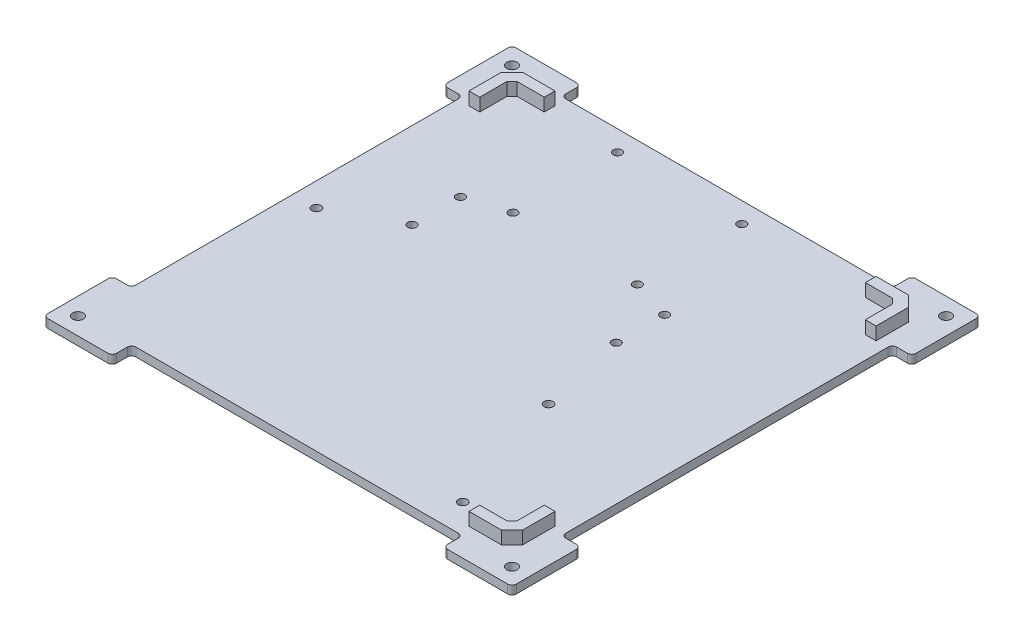
SolidWorks part; units mm, degrees
ref_plane "Plan de face" through (0, 0, 0) normal (0, 0, 1) x (1, 0, 0)
ref_plane "Plan de dessus" through (0, 0, 0) normal (0, 1, 0) x (1, 0, 0)
ref_plane "Plan de droite" through (0, 0, 0) normal (1, 0, 0) x (0, 0, -1)
sketch "Esquisse1" plane through (0, 0, 0) normal (0, 1, 0) x (1, 0, 0)
  line L20 (32, 234.4934) -> (32, -21.6261) construction
  line L21 (0, 0) -> (218, 0) construction
  line L22 (0, 0) -> (0, 218) construction
  line L23 (0, 218) -> (218, 218) construction
  line L24 (218, 0) -> (218, 218) construction
  line L25 (9, 209) -> (209, 209) construction
  line L26 (9, 209) -> (9, 9) construction
  line L27 (9, 9) -> (209, 9) construction
  line L28 (209, 209) -> (209, 9) construction
  line L29 (186, 234.4934) -> (186, -24.8818) construction
  line L30 (-33.4451, 186) -> (261.3817, 186) construction
  line L31 (-37.0626, 32) -> (249.4439, 32) construction
  line L32 (0, 218) -> (0, 186)
  line L33 (0, 186) -> (9, 186)
  line L35 (9, 32) -> (0, 32)
  line L36 (0, 32) -> (0, 0)
  line L37 (0, 0) -> (32, 0)
  line L38 (32, 0) -> (32, 9)
  line L39 (32, 9) -> (186, 9)
  line L40 (186, 9) -> (186, 0)
  line L41 (186, 0) -> (218, 0)
  line L42 (218, 0) -> (218, 32)
  line L43 (218, 32) -> (209, 32)
  line L44 (209, 32) -> (209, 186)
  line L45 (209, 186) -> (218, 186)
  line L46 (218, 186) -> (218, 218)
  line L47 (218, 218) -> (186, 218)
  line L48 (186, 218) -> (186, 209)
  line L50 (32, 209) -> (32, 218)
  line L51 (32, 218) -> (0, 218)
  line L60 (186, 209) -> (32, 209)
  line L61 (9, 186) -> (9, 32)
  circle A0 centre (8, 210) radius 2.5
  circle A1 centre (210, 210) radius 2.5
  circle A2 centre (210, 8) radius 2.5
  circle A3 centre (8, 8) radius 2.5
  point P35 (109, 109)
  point P45 (109, 109)
  point P54 (109, 109)
  dimension "D11" = 5
  dimension "D1" = 218
  dimension "D2" = 218
  dimension "D3" = 9
  dimension "D4" = 9
  dimension "D5" = 9
  dimension "D6" = 9
  dimension "D7" = 32
  dimension "D8" = 32
  dimension "D9" = 32
  dimension "D10" = 32
  dimension "D12" = 8
  dimension "D13" = 8
  dimension "D14" = 4
extrude "Boss.-Extru.1" add sketch "Esquisse1" along normal blind 4
sketch "Esquisse2" plane through (0, 4, 0) normal (0, 1, 0) x (1, 0, 0)
  line L0 (32, 9) -> (186, 9) construction
  line L1 (204, 14) -> (14, 14) construction
  line L2 (204, 14) -> (204, 204) construction
  line L3 (204, 204) -> (14, 204) construction
  line L4 (14, 14) -> (14, 204) construction
  line L5 (209, 32) -> (209, 186) construction
  line L8 (204, 109) -> (14, 109) construction
  line L9 (204, 122.5) -> (14, 122.5) construction
  line L10 (144, 145) -> (49, 145) construction
  line L11 (96.5, 145) -> (96.5, 204) construction
  line L13 (9, 186) -> (9, 32) construction
  line L14 (186, 209) -> (32, 209) construction
  circle A3 centre (172.5, 22.6) radius 2.1
  circle A4 centre (153, 82) radius 2.1
  circle A5 centre (20, 107) radius 2.1
  circle A6 centre (49, 122.5) radius 2
  circle A7 centre (144, 122.5) radius 2
  circle A8 centre (144, 145) radius 2
  circle A9 centre (49, 145) radius 2
  circle A10 centre (67.6, 199.5) radius 2
  circle A11 centre (67.6, 150.9) radius 2
  circle A12 centre (125.4, 150.9) radius 2
  circle A13 centre (125.4, 199.5) radius 2
  point P12 (204, 122.5)
  dimension "D5" = 108.5
  dimension "D6" = 35
  dimension "D7" = 95
  dimension "D8" = 4
  dimension "D9" = 4
  dimension "D10" = 22.5
  dimension "D12" = 4
  dimension "D13" = 4
  dimension "D14" = 4
  dimension "D15" = 4
  dimension "D1" = 5
  dimension "D2" = 5
  dimension "D3" = 5
  dimension "D4" = 5
  dimension "D11" = 22.5
  dimension "D16" = 4.5
  dimension "D17" = 48.6
  dimension "D18" = 28.9
extrude "Enlèv. mat.-Extru.1" cut sketch "Esquisse2" against normal blind 4
sketch "Esquisse4" plane through (0, 4, 0) normal (0, 1, 0) x (1, 0, 0)
  line L0 (198.7, 14.3) -> (183.7, 14.3)
  line L1 (183.7, 14.3) -> (183.7, 19.3)
  line L4 (198.7, 34.3) -> (203.7, 34.3)
  line L5 (203.7, 34.3) -> (203.7, 19.3)
  line L6 (32, 9) -> (186, 9) construction
  line L7 (209, 32) -> (209, 186) construction
  line L8 (203.7, 19.3) -> (198.7, 14.3)
  line L9 (198.7, 21.6468) -> (196.3532, 19.3)
  line L10 (198.7, 34.3) -> (198.7, 21.6468)
  line L11 (196.3532, 19.3) -> (183.7, 19.3)
  line L20 (19.3, 203.7) -> (34.3, 203.7)
  line L21 (34.3, 203.7) -> (34.3, 198.7)
  line L22 (19.3, 183.7) -> (14.3, 183.7)
  line L23 (14.3, 183.7) -> (14.3, 198.7)
  line L24 (14.3, 198.7) -> (19.3, 203.7)
  line L25 (19.3, 196.3532) -> (21.6468, 198.7)
  line L26 (19.3, 183.7) -> (19.3, 196.3532)
  line L27 (21.6468, 198.7) -> (34.3, 198.7)
  line L28 (203.7, 198.7) -> (203.7, 183.7)
  line L29 (203.7, 183.7) -> (198.7, 183.7)
  line L30 (183.7, 198.7) -> (183.7, 203.7)
  line L31 (183.7, 203.7) -> (198.7, 203.7)
  line L32 (198.7, 203.7) -> (203.7, 198.7)
  line L33 (196.3532, 198.7) -> (198.7, 196.3532)
  line L34 (183.7, 198.7) -> (196.3532, 198.7)
  line L35 (198.7, 196.3532) -> (198.7, 183.7)
  line L36 (34.3, 19.3) -> (21.6468, 19.3) [skipped]
  line L37 (34.3, 14.3) -> (19.3, 14.3) [skipped]
  line L38 (34.3, 19.3) -> (34.3, 14.3) [skipped]
  line L39 (19.3, 14.3) -> (14.3, 19.3) [skipped]
  line L40 (21.6468, 19.3) -> (19.3, 21.6468) [skipped]
  line L41 (19.3, 21.6468) -> (19.3, 34.3) [skipped]
  line L42 (14.3, 19.3) -> (14.3, 34.3) [skipped]
  line L43 (14.3, 34.3) -> (19.3, 34.3) [skipped]
  point P4 (109, 109)
  point P40 (109, 109)
  dimension "D1" = 5.3
  dimension "D2" = 5.3
  dimension "D3" = 5
  dimension "D4" = 5
  dimension "D5" = 20
  dimension "D6" = 20
  dimension "D7" = 4
extrude "Boss.-Extru.2" add sketch "Esquisse4" along normal blind 6
fillet "Congé1" radius 2 20 edges at (0, 2, -186) (32, 2, -218) (0, 2, -218) (0, 2, -32) (32, 2, -9) (0, 2, 0) (32, 2, 0) (186, 2, -9) (186, 2, 0) (209, 2, -32) (218, 2, -32) (218, 2, 0) (209, 2, -186) (218, 2, -186) (218, 2, -218) (186, 2, -218) (9, 2, -186) (9, 2, -32) (186, 2, -209) (32, 2, -209)
